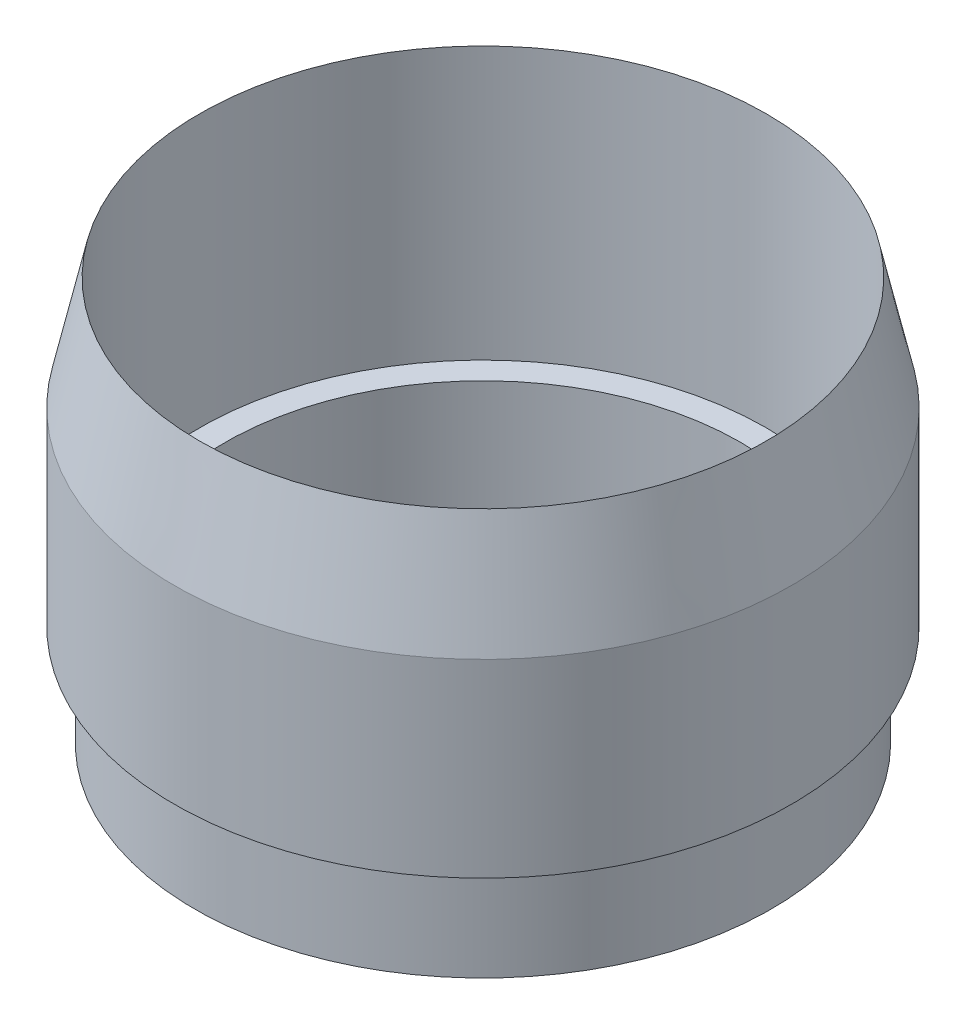
SolidWorks part; units mm, degrees
ref_plane "Front Plane" through (0, 0, 0) normal (0, 0, 1) x (1, 0, 0)
ref_plane "Top Plane" through (0, 0, 0) normal (0, 1, 0) x (1, 0, 0)
ref_plane "Right Plane" through (0, 0, 0) normal (1, 0, 0) x (0, 0, -1)
sketch "Sketch1" plane through (0, 0, 0) normal (0, 0, 1) x (1, 0, 0)
  line L1 (-30.616, 13) -> (-30.616, 10)
  line L2 (-30.616, 10) -> (-28.616, 10)
  line L3 (-28.616, 10) -> (-28.616, 0)
  line L4 (-28.616, 0) -> (-25.616, 0)
  line L7 (-28.135, 40) -> (-28.135, 13)
  line L8 (-28.135, 13) -> (-25.616, 13)
  line L9 (-25.616, 13) -> (-25.616, 0)
  line L10 (-30.616, 13) -> (-30.616, 28.8089)
  line L11 (-30.616, 28.8089) -> (-28.135, 40)
  line L12 (0, 0) -> (0, 50000) construction
  dimension "D1" = 30
  dimension "D2" = 2
  dimension "D3" = 3
  dimension "D4" = 28.135
  dimension "D5" = 10
  dimension "D6" = 28.616
  dimension "D7" = 12.5
  dimension "D8" = 3
revolve "Revolve1" add sketch "Sketch1" angle 360 about L12
